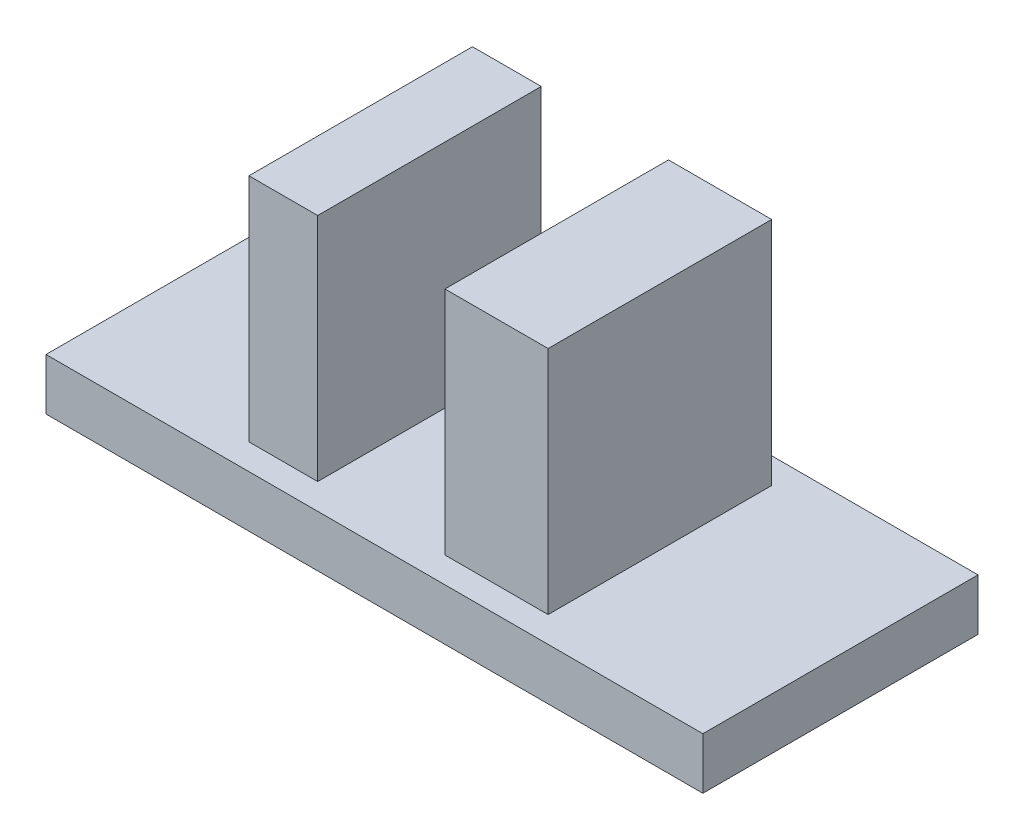
SolidWorks part; units mm, degrees
ref_plane "Ebene vorne" through (0, 0, 0) normal (0, 0, 1) x (1, 0, 0)
ref_plane "Ebene oben" through (0, 0, 0) normal (0, 1, 0) x (1, 0, 0)
ref_plane "Ebene rechts" through (0, 0, 0) normal (1, 0, 0) x (0, 0, -1)
sketch "Skizze1" plane through (0, 0, 0) normal (0, 1, 0) x (1, 0, 0)
  line L1 (-95.5, -40) -> (95.5, -40)
  line L2 (-95.5, -40) -> (-95.5, 40)
  line L3 (-95.5, 40) -> (95.5, 40)
  line L4 (95.5, -40) -> (95.5, 40)
  line L5 (-95.5, -40) -> (95.5, 40) construction
  line L6 (-95.5, 40) -> (95.5, -40) construction
  circle A0 centre (55.5, 0) radius 40
  point P0 (0, 0)
  dimension "D1" = 151
  dimension "D2" = 80
extrude "Aufsatz-Linear austragen1" add sketch "Skizze1" along normal blind 15 contours A0 L3 L2 L1 | A0 | A0 L4 L3 | A0 L1 L4
sketch "Skizze2" plane through (0, 15, 0) normal (0, 1, 0) x (1, 0, 0)
  line L1 (13, -32.5) -> (43, -32.5)
  line L2 (13, -32.5) -> (13, 32.5)
  line L3 (13, 32.5) -> (43, 32.5)
  line L4 (43, -32.5) -> (43, 32.5)
  line L5 (13, -32.5) -> (43, 32.5) construction
  line L6 (13, 32.5) -> (43, -32.5) construction
  line L10 (-44, -32.5) -> (-24, -32.5)
  line L11 (-44, -32.5) -> (-44, 32.5)
  line L12 (-44, 32.5) -> (-24, 32.5)
  line L13 (-24, -32.5) -> (-24, 32.5)
  line L14 (-44, -32.5) -> (-24, 32.5) construction
  line L15 (-44, 32.5) -> (-24, -32.5) construction
  line L17 (95.5, -40) -> (95.5, 40) construction
  line L18 (-95.5, 40) -> (95.5, 40) construction
  line L19 (-95.5, -40) -> (95.5, -40) construction
  circle A0 centre (55.5, 0) radius 40
  point P0 (28, 0)
  point P14 (-34, 0)
  point P19 (0, 0)
  dimension "D1" = 30
  dimension "D2" = 65
  dimension "D3" = 12.5
  dimension "D4" = 87
  dimension "D5" = 37
  dimension "D6" = 65
extrude "Aufsatz-Linear austragen2" add sketch "Skizze2" along normal blind 67 contours A0 L3 L2 L1 | L3 A0 L1 L4 | L10 L13 L12 L11
